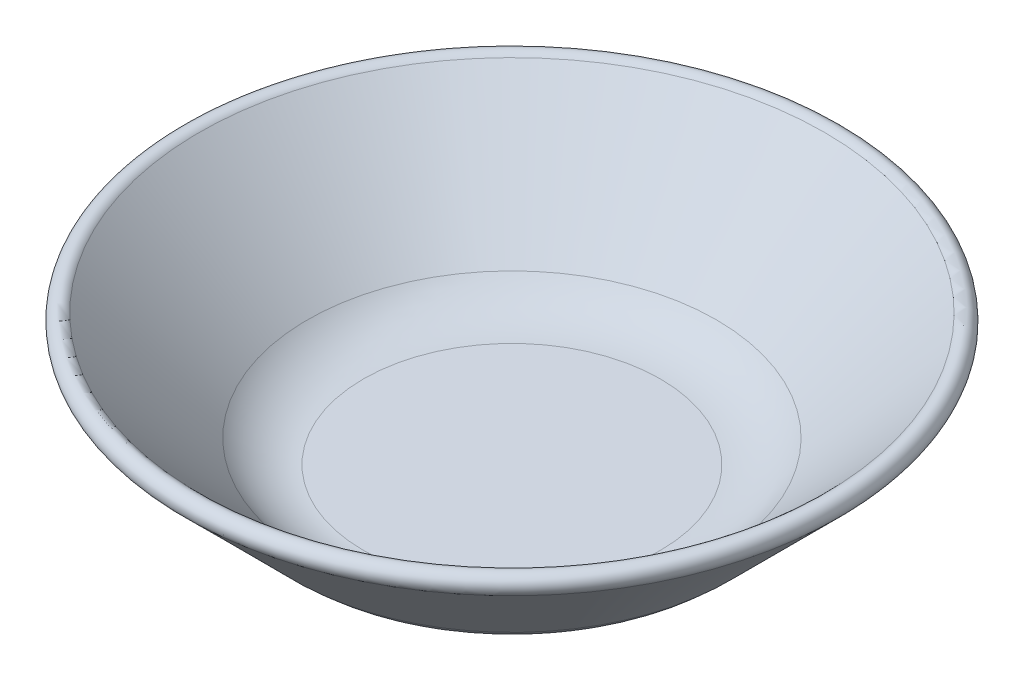
SolidWorks part; units mm, degrees
ref_plane "Front Plane" through (0, 0, 0) normal (0, 0, 1) x (1, 0, 0)
ref_plane "Top Plane" through (0, 0, 0) normal (0, 1, 0) x (1, 0, 0)
ref_plane "Right Plane" through (0, 0, 0) normal (1, 0, 0) x (0, 0, -1)
sketch "Sketch1" plane through (0, 0, 0) normal (0, 0, 1) x (1, 0, 0)
  line L0 (0, 0) -> (0, 83.0851) construction
  line L1 (0, 0) -> (37.5, 0)
  line L2 (55.1777, 7.3223) -> (82.5, 34.6447)
  line L3 (5, 5) -> (37.5, 5) construction
  line L4 (0, 5) -> (37.5, 5)
  line L5 (51.6421, 10.8579) -> (78.9645, 38.1802)
  line L6 (5, 5) -> (5, 83.0851) construction
  line L7 (77.6269, 39.5177) -> (87.3731, 29.7716) construction
  line L8 (55.1777, 7.3223) -> (104.3432, 56.4878) construction
  line L9 (0, 5) -> (0, 0)
  line L10 (51.6421, 10.8579) -> (100.8076, 60.0234) construction
  arc A0 (37.5, 0) -> (55.1777, 7.3223) centre (37.5, 25) ccw
  arc A1 (37.5, 5) -> (51.6421, 10.8579) centre (37.5, 25) ccw
  arc A3 (82.5, 34.6447) -> (78.9645, 38.1802) centre (80.7322, 36.4124) ccw
  point P19 (82.5, 34.6447)
  dimension "D3" = 25
  dimension "D1" = 135
  dimension "D2" = 75
  dimension "D5" = 165
  dimension "D4" = 5
revolve "Revolve1" add sketch "Sketch1" angle 360 about L0
